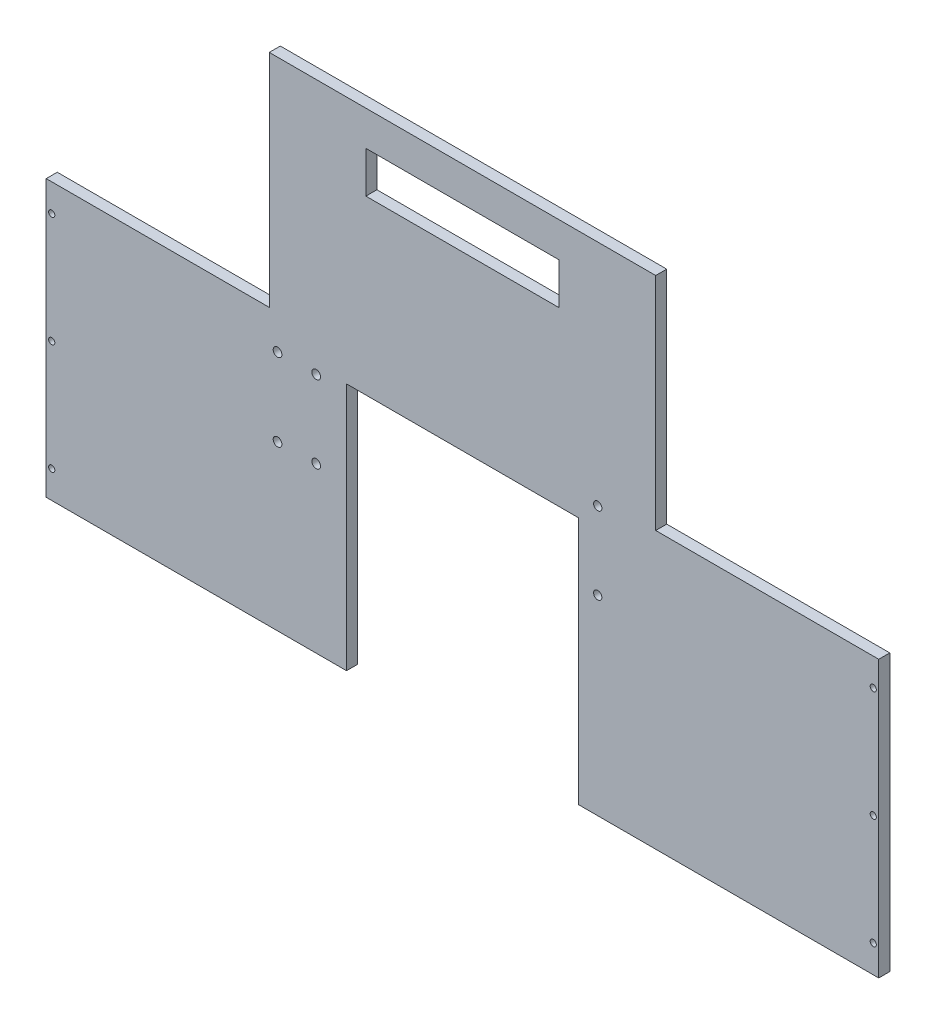
SolidWorks part; units mm, degrees
ref_plane "Front Plane" through (0, 0, 0) normal (0, 0, 1) x (1, 0, 0)
ref_plane "Top Plane" through (0, 0, 0) normal (0, 1, 0) x (1, 0, 0)
ref_plane "Right Plane" through (0, 0, 0) normal (1, 0, 0) x (0, 0, -1)
sketch "Sketch1" plane through (0, 0, 0) normal (0, 0, 1) x (1, 0, 0)
  line L0 (0, 0) -> (0, 228.6)
  line L1 (0, 228.6) -> (177.8, 228.6)
  line L2 (177.8, 228.6) -> (177.8, 0)
  line L3 (177.8, 0) -> (142.24, 0)
  line L4 (142.24, 0) -> (142.24, 114.3)
  line L5 (142.24, 114.3) -> (35.56, 114.3)
  line L6 (35.56, 114.3) -> (35.56, 0)
  line L7 (35.56, 0) -> (0, 0)
  dimension "D1" = 177.8
  dimension "D2" = 228.6
  dimension "D3" = 35.56
  dimension "D4" = 35.56
  dimension "D6" = 114.3
extrude "Boss-Extrude1" add sketch "Sketch1" along normal blind 5.08
ref_plane "Plane1" through (0, 0, 0) normal (0, 0, -1) x (-1, 0, 0)
sketch "Sketch2" plane through (0, 0, 0) normal (0, 0, -1) x (-1, 0, 0)
  line L0 (-35.56, 114.3) -> (-35.56, 111.0716) construction
  line L5 (-21.59, 111.0716) -> (-3.811, 111.0716)
  line L6 (-35.56, 111.0716) -> (-21.59, 111.0716) construction
  line L16 (-177.8, 0) -> (-241.2544, 0)
  line L17 (-142.24, 0) -> (-177.8, 0) construction
  line L18 (-241.2544, 0) -> (-241.2544, 228.6)
  line L19 (-177.8, 228.6) -> (0, 228.6) construction
  line L20 (0, 0) -> (-12.7245, 0)
  line L21 (0, 0) -> (-35.56, 0) construction
  line L23 (-21.59, 111.0716) -> (-21.59, 75.5116)
  line L25 (-3.811, 111.0716) -> (-3.811, 75.3204)
  circle A0 centre (-21.59, 111.0716) radius 2
  circle A1 centre (-3.811, 111.0716) radius 2
  circle A2 centre (-21.59, 75.5116) radius 2
  circle A3 centre (-3.811, 75.3204) radius 2
  point P16 (-21.59, 75.5116)
  point P18 (-21.59, 111.0716)
  point P19 (-3.811, 111.0716)
  point P20 (-3.811, 75.3204)
  point P43 (-21.59, 75.5116)
  dimension "D1" = 35.56
  dimension "D2" = 17.78
  dimension "D3" = 13.97
extrude "Cut-Extrude1" cut sketch "Sketch2" against normal blind 5.08
sketch "Sketch3" plane through (0, 0, 0) normal (0, 0, -1) x (-1, 0, 0)
  line L0 (-142.24, 0) -> (-177.8, 0) construction
  line L11 (-142.24, 114.3) -> (-177.8, 114.3) construction
  line L12 (-177.8, 0) -> (-177.8, 228.6) construction
  line L13 (-177.8, 114.3) -> (-177.8, 87.884) construction
  line L14 (-177.8, 87.884) -> (-142.24, 87.884) construction
  line L15 (-142.24, 114.3) -> (-142.24, 0) construction
  line L16 (-142.24, 87.884) -> (-142.24, 123.444) construction
  line L17 (-142.24, 123.444) -> (-151.1225, 123.444) construction
  line L18 (-151.1225, 123.444) -> (-151.1225, 87.884) construction
  circle A4 centre (-151.1225, 123.444) radius 1.905
  circle A5 centre (-151.1225, 87.884) radius 1.905
  dimension "D2" = 3.81
  dimension "D3" = 3.81
  dimension "D1" = 87.884
  dimension "D5" = 35.56
extrude "Cut-Extrude2" cut sketch "Sketch3" against normal blind 5.08
sketch "Sketch4" plane through (0, 0, 0) normal (0, 0, -1) x (-1, 0, 0)
  line L1 (0, 127) -> (102.616, 127)
  line L2 (0, 127) -> (0, 0)
  line L3 (0, 0) -> (102.616, 0)
  line L4 (102.616, 127) -> (102.616, 0)
  line L5 (-177.8, 127) -> (-280.416, 127)
  line L6 (-177.8, 127) -> (-177.8, 0)
  line L7 (-177.8, 0) -> (-280.416, 0)
  line L8 (-280.416, 127) -> (-280.416, 0)
  dimension "D1" = 102.616
  dimension "D2" = 102.616
  dimension "D3" = 127
  dimension "D4" = 127
extrude "Boss-Extrude2" add sketch "Sketch4" against normal blind 5.08
sketch "Sketch8" plane through (0, 0, 0) normal (0, 0, -1) x (-1, 0, 0)
  line L1 (-177.8, 228.6) -> (0, 228.6) construction
  line L3 (-133.35, 212.598) -> (-44.45, 212.598)
  line L4 (-133.35, 212.598) -> (-133.35, 193.548)
  line L5 (-133.35, 193.548) -> (-44.45, 193.548)
  line L6 (-44.45, 212.598) -> (-44.45, 193.548)
  dimension "D5" = 19.05
  dimension "D6" = 88.9
  dimension "D7" = 16.002
extrude "Cut-Extrude3" cut sketch "Sketch8" against normal blind 50.8
sketch "Sketch9" plane through (0, 0, 0) normal (0, 0, -1) x (-1, 0, 0)
  line L0 (-275.336, 127) -> (-275.336, 0) construction
  line L1 (-177.8, 127) -> (-280.416, 127) construction
  line L2 (-142.24, 0) -> (-280.416, 0) construction
  line L3 (-280.416, 127) -> (-280.416, 0) construction
  line L4 (-277.876, 127) -> (-277.876, 0) construction
  line L5 (97.536, 127) -> (97.536, 0) construction
  line L6 (102.616, 127) -> (0, 127) construction
  line L7 (102.616, 0) -> (-35.56, 0) construction
  line L8 (102.616, 0) -> (102.616, 127) construction
  line L9 (100.076, 127) -> (100.076, 0) construction
  circle A0 centre (100.076, 12.7) radius 1.4224
  circle A1 centre (100.076, 63.5) radius 1.4224
  circle A2 centre (100.076, 114.3) radius 1.4224
  circle A3 centre (-277.876, 63.5) radius 1.4224
  circle A4 centre (-277.876, 114.3) radius 1.4224
  circle A5 centre (-277.876, 12.7) radius 1.4224
  dimension "D5" = 50.8
  dimension "D7" = 50.8
  dimension "D1" = 5.08
  dimension "D2" = 2.54
  dimension "D3" = 5.08
  dimension "D4" = 2.54
  dimension "D6" = 50.8
  dimension "D8" = 50.8
extrude "Cut-Extrude4" cut sketch "Sketch9" against normal blind 10.16
